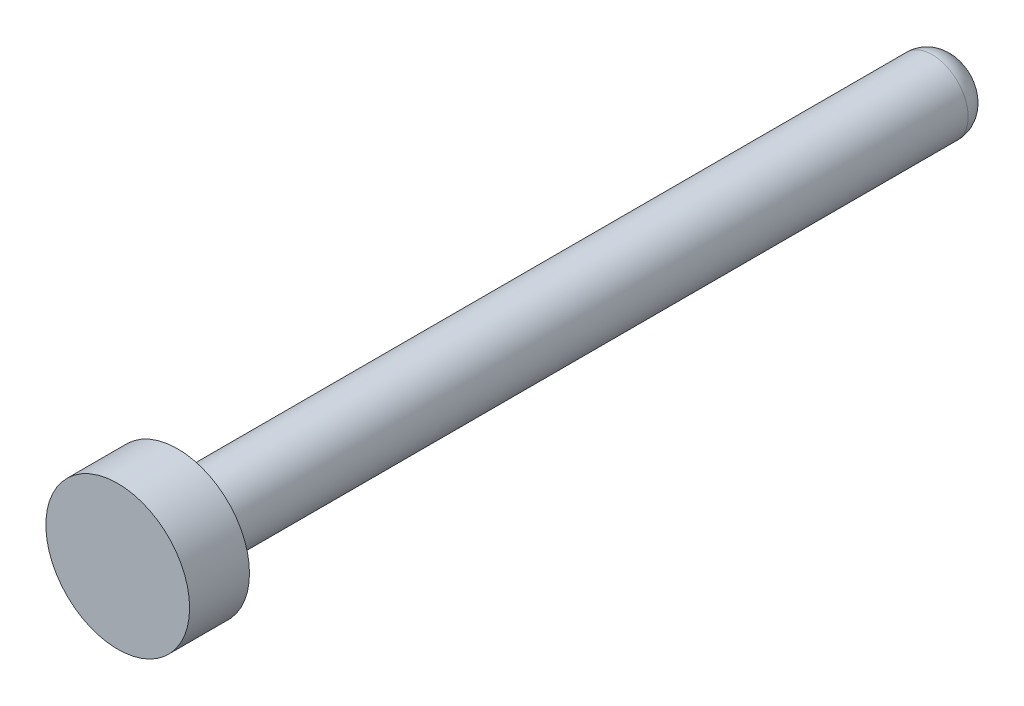
SolidWorks part; units mm, degrees
ref_plane "Front" through (0, 0, 0) normal (0, 0, 1) x (1, 0, 0)
ref_plane "Top" through (0, 0, 0) normal (0, 1, 0) x (1, 0, 0)
ref_plane "Right" through (0, 0, 0) normal (1, 0, 0) x (0, 0, -1)
sketch "Sketch1" plane through (0, 0, 0) normal (0, 0, 1) x (1, 0, 0)
  circle A0 centre (0, 0) radius 3
  dimension "D1" = 6
extrude "Boss-Extrude1" add sketch "Sketch1" along normal blind 65
sketch "Sketch2" plane through (0, 0, 65) normal (0, 0, 1) x (1, 0, 0)
  circle A0 centre (0, 0) radius 6
  dimension "D1" = 12
extrude "Boss-Extrude2" add sketch "Sketch2" along normal blind 5
fillet "Fillet1" radius 2 1 edges at (3, 0, 0)
